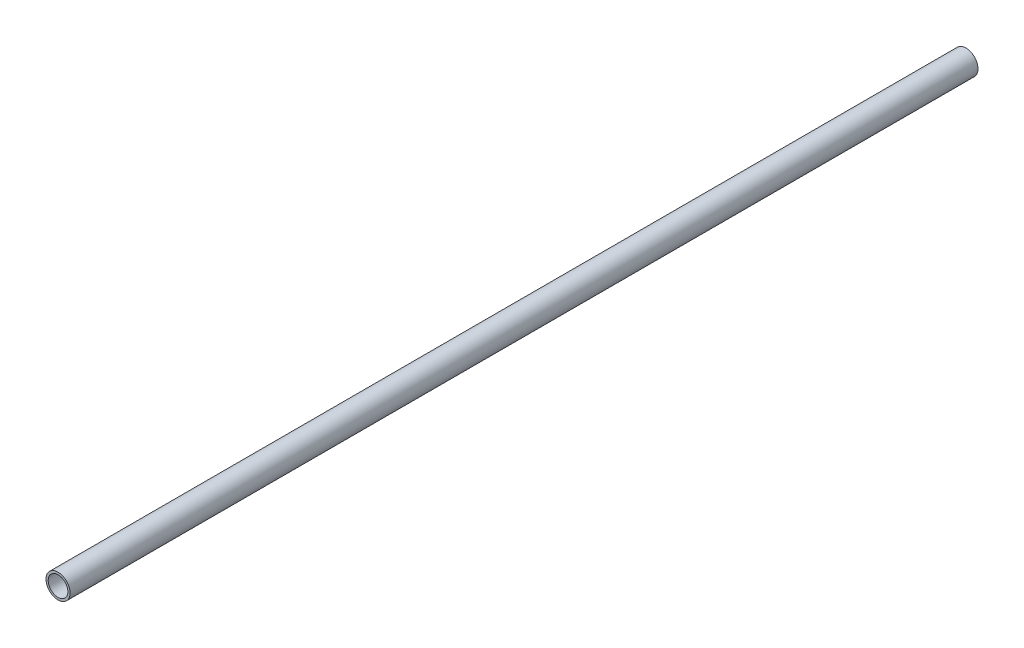
SolidWorks part; units mm, degrees
ref_plane "Front Plane" through (0, 0, 0) normal (0, 0, 1) x (1, 0, 0)
ref_plane "Top Plane" through (0, 0, 0) normal (0, 1, 0) x (1, 0, 0)
ref_plane "Right Plane" through (0, 0, 0) normal (1, 0, 0) x (0, 0, -1)
sketch "Sketch1" plane through (0, 0, 0) normal (0, 0, 1) x (1, 0, 0)
  circle A0 centre (0, 0) radius 4.05
  dimension "D1" = 8.1
extrude "Boss-Extrude1" add sketch "Sketch1" along normal mid plane 305
sketch "Sketch2" plane through (0, 0, 152.5) normal (0, 0, 1) x (1, 0, 0)
  circle A0 centre (0, 0) radius 3.3
  dimension "D1" = 6.6
extrude "Cut-Extrude1" cut sketch "Sketch2" against normal blind 20 contours A0
mirror "Mirror1" about plane through (0, 0, 0) normal (0, 0, 1) of "Cut-Extrude1"
equation "\"wheel base\" = 1561mm "
equation "\"track\" = 1354mm "
equation "\"turning radius\" = 2000mm "
equation "\"steering arm length\" = 100mm "
equation "\"turn to lock\" = 0.75mm "
equation "\"shaft inner diameter\"= 15mm "
equation "\"shaft outer diameter\"= 20mm "
equation "\"column angle\" = 45deg "
equation "\"keyway_height\" = 1.39mm "
equation "\"keyway_width\" = 2.78mm "
equation "\"keyway_length\" = 30mm "
equation "\"steering column length\" = 555mm "
equation "\"steering wheel bolt width\" = 6mm "
equation "\"steering wheel bolt length\" = 40mm "
equation "\"bushing length\" = 40mm "
equation "\"bushing thickness\" = 3mm "
equation "\"u_joint clearance\" = 30mm "
equation "\"u_joint thickness\" = 7.5mm "
equation "\"horizontal shaft length\" = 90mm "
equation "\"short_bearing_outer_width\" = 10mm "
equation "\"column bushing diameter\" = \"primary shaft small diameter\" + 4 "
equation "\"column bushing distance\" = \"steering column length\"/4 "
equation "\"pinion width\" = 26.5mm "
equation "\"pin hole diameter\" = 10mm "
equation "\"rack hole to hole\" = 500mm "
equation "\"rack length\" = \"rack hole to hole\" + \"pin hole diameter\"*2 "
equation "\"max turning angle\" = atn(\"wheel base\" / (\"turning radius\" - 0.5 * \"track\")) "
equation "\"max travel\" = 2 * \"steering arm length\" * sin(0.5 * \"max turning angle\") "
equation "\"pitch diameter\" = \"max travel\"/(pi * \"turn to lock\") "
equation "\"number of teeth\" = 18mm "
equation "\"module\" = \"pitch diameter\" / \"number of teeth\" "
equation "\"pressure angle\" = 20deg "
equation "\"tie rod length\" = 305mm "
equation "\"D1@Sketch1\"=\"tie rod outer diameter\""
equation "\"D1@Boss-Extrude1\"=\"tie rod length\""
equation "\"D1@Sketch2\"=\"tie rod inner diameter\""
equation "\"primary shaft small diameter\" = 16mm "
equation "\"primary shaft large diameter\" = 24mm "
equation "\"secondary shaft small diameter\" = 16mm "
equation "\"secondary shaft large diameter\" = 25mm "
equation "\"tie rod inner diameter\" = 6.6mm "
equation "\"tie rod outer diameter\" = 8.1mm "
